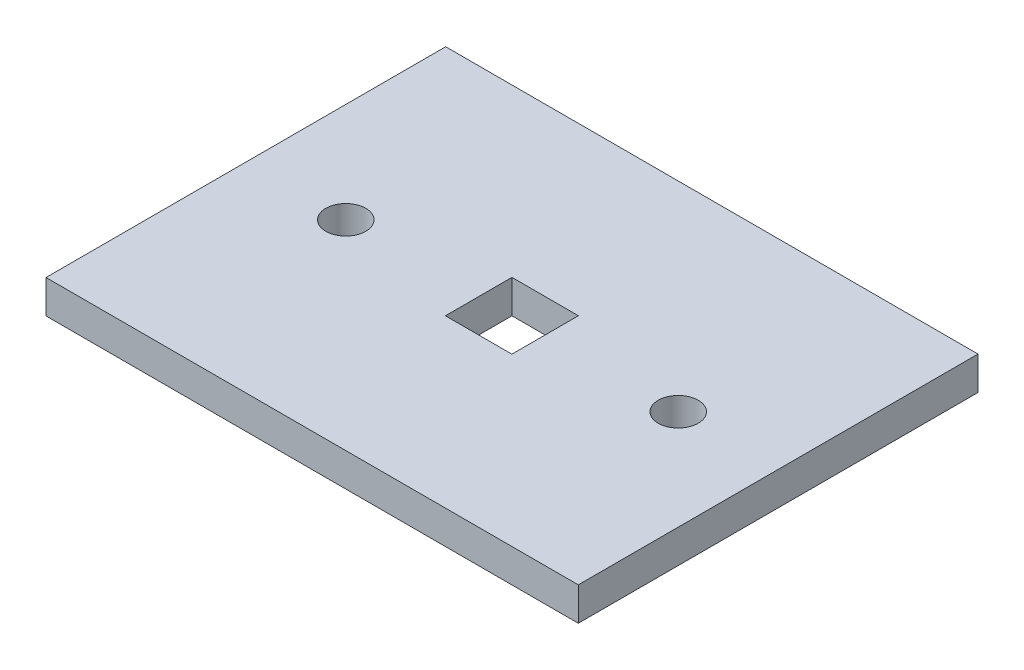
SolidWorks part; units mm, degrees
ref_plane "Front Plane" through (0, 0, 0) normal (0, 0, 1) x (1, 0, 0)
ref_plane "Top Plane" through (0, 0, 0) normal (0, 1, 0) x (1, 0, 0)
ref_plane "Right Plane" through (0, 0, 0) normal (1, 0, 0) x (0, 0, -1)
sketch "Sketch3" plane through (0, 0, 0) normal (0, 1, 0) x (1, 0, 0)
  line L0 (-45.5122, 37.7561) -> (-45.5122, -82.2439)
  line L1 (-45.5122, -82.2439) -> (114.2927, -82.2439)
  line L2 (114.2927, -82.2439) -> (114.2927, 37.7561)
  line L3 (114.2927, 37.7561) -> (-45.5122, 37.7561)
  dimension "D1" = 120
extrude "Boss-Extrude1" add sketch "Sketch3" along normal blind 10 contours L3 L0 L1 L2
sketch "Sketch4" plane through (0, 10, 0) normal (0, 1, 0) x (1, 0, 0)
  line L4 (44.3573, -22.2439) -> (44.3573, -32.2489)
  line L5 (44.3573, -32.2489) -> (24.3985, -32.2489)
  line L6 (24.3985, -32.2489) -> (24.3985, -12.269)
  line L7 (24.3985, -12.269) -> (44.3573, -12.269)
  line L8 (44.3573, -12.269) -> (44.3573, -22.2439)
extrude "Cut-Extrude1" cut sketch "Sketch4" against normal blind 20 contours L4 L5 L6 L7 L8
sketch "Sketch5" plane through (0, 10, 0) normal (0, 1, 0) x (1, 0, 0)
  circle A0 centre (84.2927, -22.2439) radius 6
  circle A1 centre (-15.5122, -22.2439) radius 6
  point P0 (0, 0)
  dimension "D3" = 12
  dimension "D4" = 12
extrude "Cut-Extrude3" cut sketch "Sketch5" against normal blind 20 contours A1 | A0
